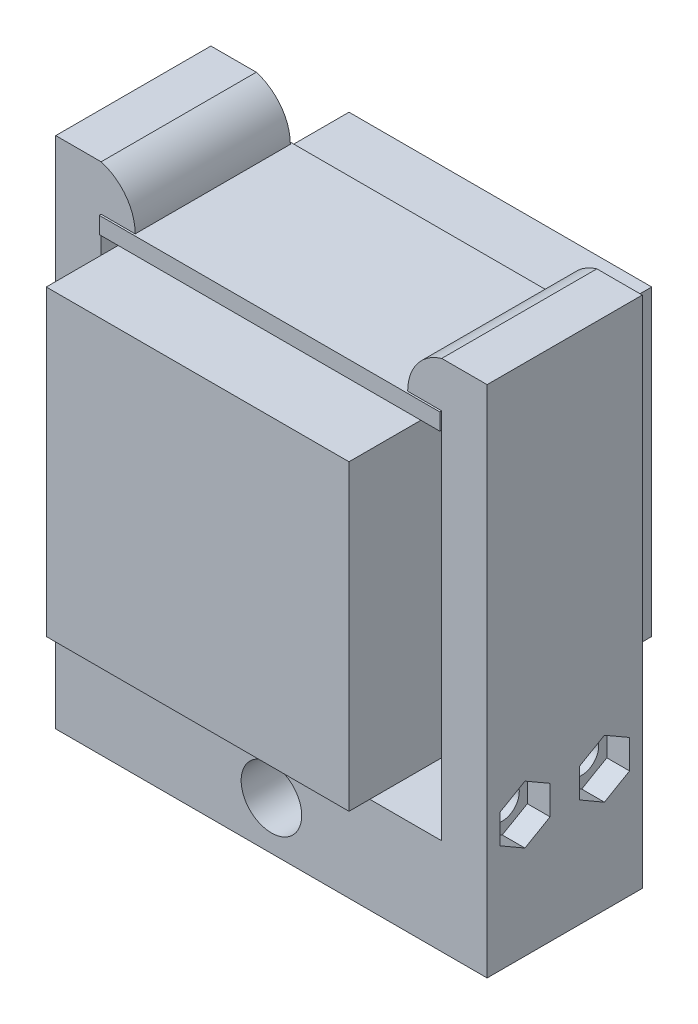
SolidWorks part; units mm, degrees
ref_plane "Front Plane" through (0, 0, 0) normal (0, 0, 1) x (1, 0, 0)
ref_plane "Top Plane" through (0, 0, 0) normal (0, 1, 0) x (1, 0, 0)
ref_plane "Right Plane" through (0, 0, 0) normal (1, 0, 0) x (0, 0, -1)
sketch "Sketch1" plane through (0, 0, 0) normal (0, 1, 0) x (1, 0, 0)
  line L9 (-22.5, -10.5) -> (22.5, -10.5)
  line L10 (-22.5, -10.5) -> (-22.5, 10.5)
  line L11 (-22.5, 10.5) -> (22.5, 10.5)
  line L12 (22.5, -10.5) -> (22.5, 10.5)
  line L13 (-22.5, -10.5) -> (22.5, 10.5) construction
  line L14 (-22.5, 10.5) -> (22.5, -10.5) construction
  point P0 (0, 0)
  point P1 (-22.4496, -13.4391)
  point P2 (0, 0)
  point P3 (0, 0)
  point P4 (0, 0)
  point P6 (54.3906, -42.45)
  point P7 (0, 0)
  dimension "D2" = 21
  dimension "D3" = 45
extrude "Boss-Extrude1" add sketch "Sketch1" along normal blind 2.2
sketch "Sketch2" plane through (0, 0, 0) normal (0, 1, 0) x (1, 0, 0)
  line L1 (-20, -20) -> (20, -20)
  line L2 (-20, -20) -> (-20, 20)
  line L3 (-20, 20) -> (20, 20)
  line L4 (20, -20) -> (20, 20)
  line L5 (-20, -20) -> (20, 20) construction
  line L6 (-20, 20) -> (20, -20) construction
  point P0 (0, 0)
  point P6 (0, 0)
  dimension "D1" = 40
  dimension "D2" = 40
extrude "Boss-Extrude2" add sketch "Sketch2" against normal blind 40 separate body
sketch "Sketch3" plane through (0, 0, 0) normal (0, 0, 1) x (1, 0, 0)
  line L1 (-22.5, -59.7) -> (22.5, -59.7)
  line L2 (-22.5, -59.7) -> (-22.5, -47)
  line L3 (-22.5, -47) -> (22.5, -47)
  line L4 (22.5, -59.7) -> (22.5, -47)
  line L5 (-22.5, -59.7) -> (22.5, -47) construction
  line L6 (-22.5, -47) -> (22.5, -59.7) construction
  line L7 (22.5, 2.2) -> (22.5, 0) construction
  line L8 (0, -22) -> (0, 22) construction
  line L10 (22.5, -59.7) -> (28.5, -59.7)
  line L11 (22.5, -59.7) -> (22.5, 0)
  line L13 (28.5, -59.7) -> (28.5, 0)
  line L16 (-28.5, -59.7) -> (-28.5, 0)
  line L17 (-22.5, -59.7) -> (-28.5, -59.7)
  line L18 (-22.5, -59.7) -> (-22.5, 0)
  line L20 (22.5, -47) -> (22.5, 0) construction
  line L21 (22, 0) -> (-22, 0) construction
  line L22 (28.5, 0) -> (28.5, 8.2)
  line L23 (28.5, 0) -> (28.5, 5.5196) construction
  line L24 (28.5, 8.2) -> (22.5, 8.2)
  line L26 (22.5, 0) -> (22.5, 2.2)
  line L27 (18, 2.2) -> (22.5, 2.2)
  line L28 (-22.5, 0) -> (-22.5, 2.2)
  line L29 (-18, 2.2) -> (-22.5, 2.2)
  line L30 (-28.5, 0) -> (-28.5, 8.2)
  line L31 (-28.5, 8.2) -> (-22.5, 8.2)
  line L32 (-22.5, 0) -> (22.5, 0) construction
  line L33 (22.5, -43.5) -> (-22.5, -43.5) construction
  line L34 (0, -40) -> (0, -47) construction
  line L35 (-20, -40) -> (20, -40) construction
  line L36 (20, -40) -> (-20, -40) construction
  line L37 (-22.5, -45.5) -> (22.5, -45.5) construction
  line L38 (-22.5, -45.5) -> (-22.5, -41.5) construction
  line L39 (-22.5, -41.5) -> (22.5, -41.5) construction
  line L40 (22.5, -45.5) -> (22.5, -41.5) construction
  line L41 (-22.5, -45.5) -> (22.5, -41.5) construction
  line L42 (-22.5, -41.5) -> (22.5, -45.5) construction
  circle A2 centre (0, -53.35) radius 4
  arc A3 (22.5, 8.2) -> (18, 2.2) centre (24.25, 2.2) ccw
  arc A4 (-22.5, 8.2) -> (-18, 2.2) centre (-24.25, 2.2) cw
  point P0 (0, -53.35)
  point P31 (0, -43.5)
  point P40 (0, -43.5)
  dimension "D8" = 8
  dimension "D2" = 12.7
  dimension "D7" = 6
  dimension "D9" = 0
  dimension "D4" = 8.2
  dimension "D5" = 0
  dimension "D6" = 4.5
  dimension "D10" = 2.2
  dimension "D3" = 4
  dimension "D11" = 1.5
extrude "Boss-Extrude3" add sketch "Sketch3" along normal mid plane 20.5 separate body
sketch "Sketch6" plane through (28.5, 0, 0) normal (1, 0, 0) x (0, 0, -1)
  line L0 (-10.25, -43.5) -> (10.25, -43.5) construction
  line L1 (-10.25, -59.7) -> (-10.25, 8.2) construction
  line L2 (10.25, -59.7) -> (10.25, 8.2) construction
  line L3 (0, 31.35) -> (0, -31.35) construction
  circle A0 centre (-5.25, -43.5) radius 2.25
  circle A1 centre (5.25, -43.5) radius 2.25
  point P8 (0, 0)
  dimension "D1" = 5
  dimension "D2" = 4.5
extrude "Cut-Extrude1" cut sketch "Sketch6" against normal through all
sketch "Sketch7" plane through (28.5, 0, 0) normal (1, 0, 0) x (0, 0, -1)
  line L0 (-5.25, -39.67) -> (-5.25, -47.33) construction
  line L1 (-1.9331, -45.415) -> (-8.5669, -41.585) construction
  line L2 (-8.5669, -45.415) -> (-1.9331, -41.585) construction
  line L3 (-8.5669, -41.585) -> (-5.25, -39.67)
  line L4 (-5.25, -39.67) -> (-1.9331, -41.585)
  line L5 (-1.9331, -41.585) -> (-1.9331, -45.415)
  line L6 (-1.9331, -45.415) -> (-5.25, -47.33)
  line L7 (-5.25, -47.33) -> (-8.5669, -45.415)
  line L8 (-8.5669, -45.415) -> (-8.5669, -41.585)
  line L9 (0, 31.35) -> (0, -31.35) construction
  line L10 (1.9331, -41.585) -> (1.9331, -45.415)
  line L11 (1.9331, -45.415) -> (5.25, -47.33)
  line L12 (5.25, -47.33) -> (8.5669, -45.415)
  line L13 (8.5669, -45.415) -> (8.5669, -41.585)
  line L14 (8.5669, -41.585) -> (5.25, -39.67)
  line L15 (5.25, -39.67) -> (1.9331, -41.585)
  circle A0 centre (-5.25, -43.5) radius 3.83 construction
  circle A1 centre (-5.25, -43.5) radius 2.25 construction
  point P13 (-5.25, -43.5)
  point P24 (-5.25, -43.5)
  dimension "D1" = 7.66
  dimension "D2" = 3
  dimension "D3" = 6
extrude "Cut-Extrude2" cut sketch "Sketch7" against normal blind 3
equation "\"D5@Sketch3\"=\"D9@Sketch3\""
